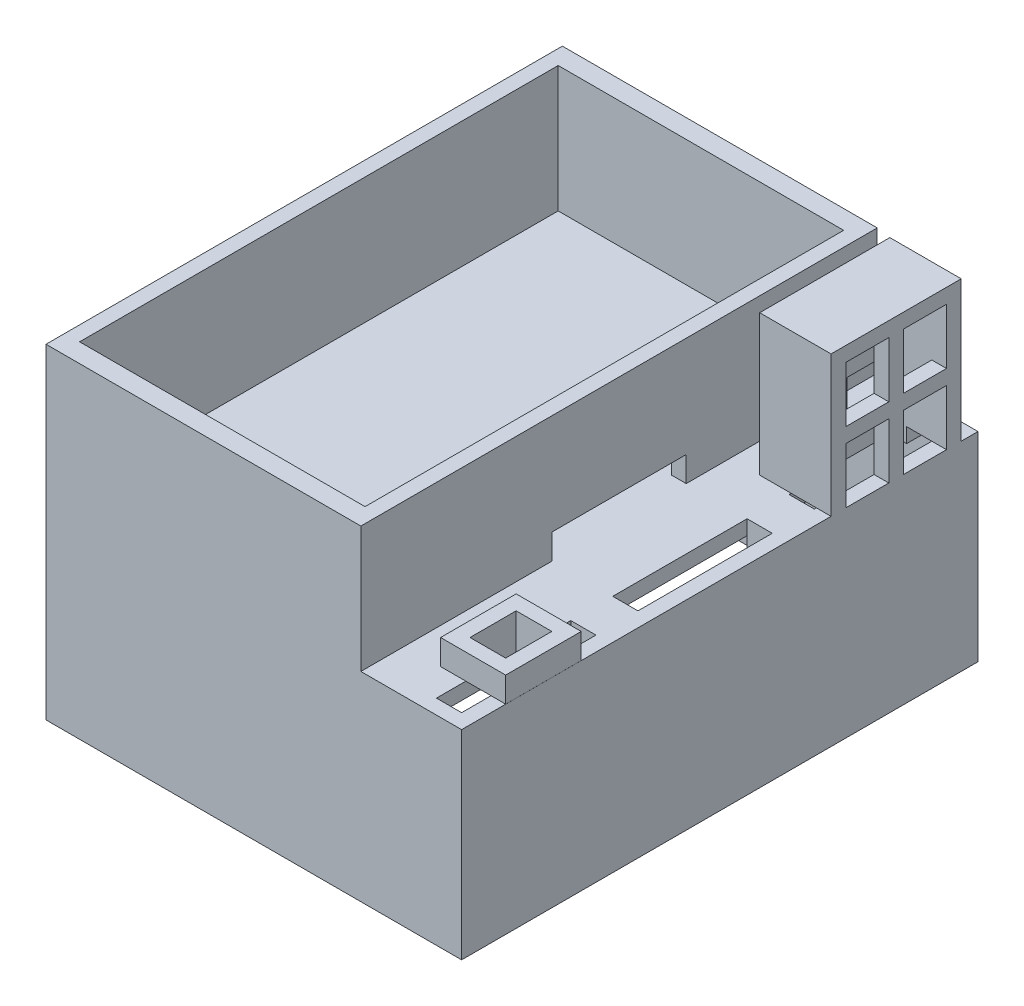
SolidWorks part; units mm, degrees
ref_plane "Front Plane" through (0, 0, 0) normal (0, 0, 1) x (1, 0, 0)
ref_plane "Top Plane" through (0, 0, 0) normal (0, 1, 0) x (1, 0, 0)
ref_plane "Right Plane" through (0, 0, 0) normal (1, 0, 0) x (0, 0, -1)
sketch "Sketch1" plane through (0, 0, 0) normal (0, 1, 0) x (1, 0, 0)
  line L1 (-138.162, -76.1412) -> (-88.662, -76.1412)
  line L2 (-138.162, -76.1412) -> (-138.162, -14.6412)
  line L3 (-138.162, -14.6412) -> (-88.662, -14.6412)
  line L4 (-88.662, -76.1412) -> (-88.662, -14.6412)
  dimension "D1" = 49.5
  dimension "D2" = 61.5
extrude "Boss-Extrude1" add sketch "Sketch1" along normal blind 23.75
sketch "Sketch2" plane through (0, 0, 0) normal (0, -1, 0) x (-1, 0, 0)
  line L0 (138.162, -76.1412) -> (88.662, -76.1412) construction
  line L1 (90.412, -74.3912) -> (136.412, -74.3912)
  line L2 (90.412, -74.3912) -> (90.412, -16.3912)
  line L3 (90.412, -16.3912) -> (136.412, -16.3912)
  line L4 (136.412, -74.3912) -> (136.412, -16.3912)
  line L5 (88.662, -76.1412) -> (88.662, -14.6412) construction
  line L6 (88.662, -14.6412) -> (138.162, -14.6412) construction
  line L7 (138.162, -14.6412) -> (138.162, -76.1412) construction
  dimension "D1" = 1.75
  dimension "D2" = 1.75
  dimension "D3" = 1.75
  dimension "D4" = 1.75
extrude "Cut-Extrude1" cut sketch "Sketch2" against normal blind 22
sketch "Sketch3" plane through (0, 22, 0) normal (0, -1, 0) x (-1, 0, 0)
  line L0 (136.412, -16.3912) -> (90.412, -16.3912) construction
  line L1 (90.412, -74.3912) -> (93.412, -74.3912)
  line L2 (90.412, -74.3912) -> (90.412, -16.3912)
  line L3 (90.412, -16.3912) -> (93.412, -16.3912)
  line L4 (93.412, -74.3912) -> (93.412, -16.3912)
  line L6 (90.412, -58.3912) -> (93.412, -58.3912)
  line L7 (90.412, -58.3912) -> (90.412, -53.3912)
  line L8 (90.412, -53.3912) -> (93.412, -53.3912)
  line L9 (93.412, -58.3912) -> (93.412, -53.3912)
  line L10 (90.412, -37.3912) -> (93.412, -37.3912)
  line L11 (90.412, -37.3912) -> (90.412, -32.3912)
  line L12 (90.412, -32.3912) -> (93.412, -32.3912)
  line L13 (93.412, -37.3912) -> (93.412, -32.3912)
  line M9 (90.412, -16.3912) -> (90.412, -74.3912)
  line M10 (90.412, -74.3912) -> (136.412, -74.3912)
  line M12 (136.412, -16.3912) -> (90.412, -16.3912)
  dimension "D1" = 3
  dimension "D2" = 5
  dimension "D3" = 5
  dimension "D4" = 16
  dimension "D5" = 16
extrude "Cut-Extrude2" cut sketch "Sketch3" against normal blind 1.75 contours L6 L2 L4 M10 | L12 L4 M9 M12 | L10 L2 L8 L4
sketch "Sketch7" plane through (0, 22, 0) normal (0, -1, 0) x (-1, 0, 0)
  line L1 (90.412, -58.3912) -> (93.412, -58.3912)
  line L2 (90.412, -58.3912) -> (90.412, -53.3912)
  line L3 (90.412, -53.3912) -> (93.412, -53.3912)
  line L4 (93.412, -58.3912) -> (93.412, -53.3912)
  line L5 (90.412, -37.3912) -> (93.412, -37.3912)
  line L6 (90.412, -37.3912) -> (90.412, -32.3912)
  line L7 (90.412, -32.3912) -> (93.412, -32.3912)
  line L8 (93.412, -37.3912) -> (93.412, -32.3912)
  point P10 (91.4714, -46.0867)
extrude "Boss-Extrude2" add sketch "Sketch7" along normal blind 4 contours L2 L1 L4 L3 | L6 L5 L8 L7
sketch "Sketch9" plane through (-93.412, 0, 0) normal (-1, 0, 0) x (0, 0, 1)
  line L0 (58.3912, 18) -> (58.3912, 22) construction
  line L1 (58.3912, 20.407) -> (53.3912, 20.407)
  line L2 (58.3912, 20.407) -> (58.3912, 22)
  line L3 (58.3912, 22) -> (53.3912, 22)
  line L4 (53.3912, 20.407) -> (53.3912, 22)
  point P7 (52.9928, 22.2027)
sketch "Sketch11" plane through (0, 23.75, 0) normal (0, 1, 0) x (1, 0, 0)
  line L0 (-138.162, -76.1412) -> (-88.662, -76.1412) construction
  line L1 (-138.162, -14.6412) -> (-100.662, -14.6412)
  line L2 (-138.162, -14.6412) -> (-138.162, -76.1412)
  line L3 (-138.162, -76.1412) -> (-100.662, -76.1412)
  line L4 (-100.662, -14.6412) -> (-100.662, -76.1412)
  dimension "D1" = 37.5
extrude "Boss-Extrude3" add sketch "Sketch11" along normal blind 15
sketch "Sketch12" plane through (0, 38.75, 0) normal (0, 1, 0) x (1, 0, 0)
  line L0 (-138.162, -14.6412) -> (-138.162, -76.1412) construction
  line L1 (-136.412, -16.8912) -> (-102.412, -16.8912)
  line L2 (-136.412, -16.8912) -> (-136.412, -73.8912)
  line L3 (-136.412, -73.8912) -> (-102.412, -73.8912)
  line L4 (-102.412, -16.8912) -> (-102.412, -73.8912)
  line L5 (-100.662, -76.1412) -> (-100.662, -14.6412) construction
  line L6 (-100.662, -14.6412) -> (-138.162, -14.6412) construction
  line L7 (-138.162, -76.1412) -> (-100.662, -76.1412) construction
  dimension "D1" = 1.75
  dimension "D2" = 1.75
  dimension "D3" = 2.25
  dimension "D4" = 2.25
extrude "Cut-Extrude3" cut sketch "Sketch12" against normal blind 15
sketch "Sketch14" plane through (0, 23.75, 0) normal (0, 1, 0) x (1, 0, 0)
  line L0 (-90.412, -58.3912) -> (-93.412, -58.3912) construction
  line L1 (-96.417, -70.8912) -> (-88.667, -70.8912)
  line L2 (-96.417, -70.8912) -> (-96.417, -61.8912)
  line L3 (-96.417, -61.8912) -> (-88.667, -61.8912)
  line L4 (-88.667, -70.8912) -> (-88.667, -61.8912)
  point P6 (-91.912, -58.3912)
  dimension "D1" = 9
  dimension "D2" = 7.75
  dimension "D3" = 3.5
  dimension "D4" = 3.245
extrude "Boss-Extrude4" add sketch "Sketch14" along normal blind 3
sketch "Sketch15" plane through (0, 26.75, 0) normal (0, 1, 0) x (1, 0, 0)
  line L0 (-96.417, -61.8912) -> (-96.417, -70.8912) construction
  line L1 (-94.667, -69.1412) -> (-90.417, -69.1412)
  line L2 (-94.667, -69.1412) -> (-94.667, -63.6412)
  line L3 (-94.667, -63.6412) -> (-90.417, -63.6412)
  line L4 (-90.417, -69.1412) -> (-90.417, -63.6412)
  line L5 (-88.667, -61.8912) -> (-96.417, -61.8912) construction
  line L6 (-88.667, -70.8912) -> (-88.667, -61.8912) construction
  line L7 (-96.417, -70.8912) -> (-88.667, -70.8912) construction
  dimension "D1" = 1.75
  dimension "D2" = 1.75
  dimension "D3" = 1.75
  dimension "D4" = 1.75
extrude "Cut-Extrude4" cut sketch "Sketch15" against normal blind 4.75
sketch "Sketch16" plane through (0, 23.75, 0) normal (0, 1, 0) x (1, 0, 0)
  line L0 (-93.412, -16.3912) -> (-90.412, -16.3912) construction
  line L1 (-97.162, -32.1412) -> (-88.662, -32.1412)
  line L2 (-97.162, -32.1412) -> (-97.162, -16.6412)
  line L3 (-97.162, -16.6412) -> (-88.662, -16.6412)
  line L4 (-88.662, -32.1412) -> (-88.662, -16.6412)
  line L5 (-93.412, -32.3912) -> (-93.412, -16.3912) construction
  point P6 (-91.912, -16.3912)
  point P9 (-93.412, -24.3912)
  dimension "D1" = 15.5
  dimension "D2" = 8.5
  dimension "D3" = 3.25
  dimension "D4" = 7.75
extrude "Boss-Extrude5" add sketch "Sketch16" along normal blind 16.75
sketch "Sketch17" plane through (-88.662, 0, 0) normal (1, 0, 0) x (0, 0, -1)
  line L0 (-32.1412, 40.5) -> (-16.6412, 40.5) construction
  line L1 (-30.3912, 38.75) -> (-25.2662, 38.75)
  line L2 (-30.3912, 38.75) -> (-30.3912, 23.75)
  line L3 (-30.3912, 23.75) -> (-25.2662, 23.75)
  line L4 (-25.2662, 38.75) -> (-25.2662, 23.75)
  line L5 (-23.5162, 38.75) -> (-18.3912, 38.75)
  line L6 (-23.5162, 38.75) -> (-23.5162, 23.75)
  line L7 (-23.5162, 23.75) -> (-18.3912, 23.75)
  line L8 (-18.3912, 38.75) -> (-18.3912, 23.75)
  line L9 (-32.1412, 40.5) -> (-32.1412, 23.75) construction
  line L10 (-16.6412, 40.5) -> (-16.6412, 23.75) construction
  line L11 (-16.6412, 23.75) -> (-14.6412, 23.75) construction
  line L12 (-76.1412, 23.75) -> (-32.1412, 23.75) construction
  line L14 (-32.1412, 32.125) -> (-16.6412, 32.125)
  line L15 (-32.1412, 32.125) -> (-32.1412, 30.375)
  line L16 (-32.1412, 30.375) -> (-16.6412, 30.375)
  line L17 (-16.6412, 32.125) -> (-16.6412, 30.375)
  point P18 (-33.1974, 25.9347)
  dimension "D1" = 1.75
  dimension "D2" = 1.75
  dimension "D3" = 1.75
  dimension "D4" = 1.75
  dimension "D5" = 0
  dimension "D6" = 0
  dimension "D7" = 5.125
  dimension "D8" = 5.125
  dimension "D9" = 1.75
  dimension "D10" = 6.625
extrude "Cut-Extrude5" cut sketch "Sketch17" against normal blind 8.5 contours L2 L14 L4 L1 | L16 L2 L3 L4 | L6 L14 L8 L5 | L16 L6 L7 L8
sketch "Sketch18" plane through (0, 23.75, 0) normal (0, 1, 0) x (1, 0, 0)
  line L0 (-93.412, -18.3912) -> (-90.412, -18.3912) construction
  line L1 (-95.412, -30.3912) -> (-90.412, -30.3912)
  line L2 (-95.412, -30.3912) -> (-95.412, -18.3912)
  line L3 (-95.412, -18.3912) -> (-90.412, -18.3912)
  line L4 (-90.412, -30.3912) -> (-90.412, -18.3912)
  line L5 (-88.662, -30.3912) -> (-88.662, -25.2662) construction
  line L6 (-93.412, -30.3912) -> (-90.412, -30.3912) construction
  point P4 (-86.5623, -17.3867)
  dimension "D1" = 0
  dimension "D2" = 1.75
  dimension "D3" = 1.75
  dimension "D4" = 0
extrude "Cut-Extrude6" cut sketch "Sketch18" against normal blind 1.75 and the other way blind 15
sketch "Sketch20" plane through (-100.662, 0, 0) normal (1, 0, 0) x (0, 0, -1)
  line L0 (-76.1412, 23.75) -> (-14.6412, 23.75) construction
  line L1 (-53.3912, 26.75) -> (-37.3912, 26.75)
  line L2 (-53.3912, 26.75) -> (-53.3912, 23.75)
  line L3 (-53.3912, 23.75) -> (-37.3912, 23.75)
  line L4 (-37.3912, 26.75) -> (-37.3912, 23.75)
  dimension "D1" = 3
  dimension "D2" = 0
  dimension "D3" = 0
extrude "Cut-Extrude7" cut sketch "Sketch20" against normal blind 1.75
